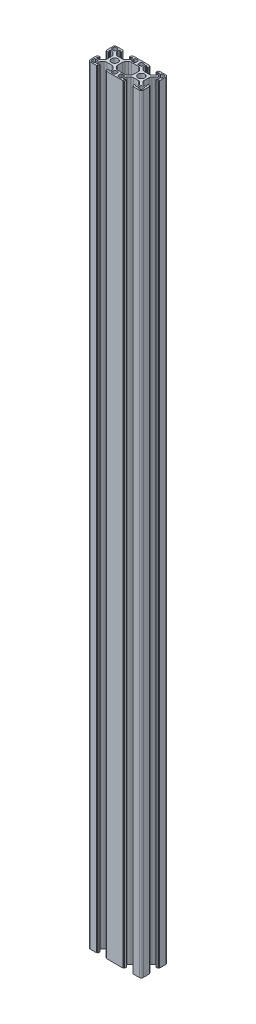
SolidWorks part; units mm, degrees
ref_plane "Спереди" through (0, 0, 0) normal (0, 0, 1) x (1, 0, 0)
ref_plane "Сверху" through (0, 0, 0) normal (0, 1, 0) x (1, 0, 0)
ref_plane "Справа" through (0, 0, 0) normal (1, 0, 0) x (0, 0, -1)
sketch "Эскиз1" plane through (0, 0, 0) normal (0, 1, 0) x (1, 0, 0)
  line L0 (-3.1522, 8.2837) -> (-1.6522, 6.7837) construction
  line L1 (18.3478, 9.7837) -> (15.3478, 6.7837) construction
  line L2 (-10.7522, 0.6837) -> (-0.7522, 10.6837) construction
  line L3 (9.2478, 4.6837) -> (11.1466, 4.6837)
  line L4 (9.2478, 0.6837) -> (19.2478, 10.6837) construction
  line L5 (16.8478, 8.2837) -> (15.3478, 9.7837) construction
  line L6 (12.5608, 5.2695) -> (13.862, 6.5707)
  line L7 (16.1478, 6.7837) -> (17.5478, 6.7837)
  line L8 (15.3478, 7.5837) -> (15.3478, 8.9837)
  line L9 (17.5478, 9.7837) -> (16.1478, 9.7837)
  line L10 (14.4478, 8.8837) -> (14.4478, 7.9849)
  line L11 (13.011, 8.757) -> (13.4914, 9.2373)
  line L12 (12.4478, 10.2328) -> (12.9478, 10.2328)
  line L13 (12.8343, 8.6837) -> (12.5478, 8.6837)
  line L14 (13.8449, 9.3837) -> (13.9478, 9.3837)
  line L15 (12.9478, 10.5337) -> (12.9478, 10.2328)
  line L16 (12.2978, 10.0828) -> (12.2978, 8.9337)
  line L17 (17.7478, 10.6837) -> (13.0978, 10.6837)
  line L18 (18.3478, 8.9837) -> (18.3478, 7.5837)
  line L19 (19.2478, 9.1837) -> (19.2478, 4.5337)
  line L20 (18.6469, 3.7337) -> (17.4978, 3.7337)
  line L21 (19.0978, 4.3837) -> (18.7969, 4.3837)
  line L22 (17.9478, 5.2808) -> (17.9478, 5.3837)
  line L23 (17.2478, 4.2702) -> (17.2478, 3.9837)
  line L24 (18.7969, 3.8837) -> (18.7969, 4.3837)
  line L25 (17.321, 4.447) -> (17.8014, 4.9273)
  line L26 (17.4478, 5.8837) -> (16.549, 5.8837)
  line L27 (13.8336, 3.9967) -> (15.1348, 5.2979)
  line L28 (13.2478, 0.6837) -> (13.2478, 2.5825)
  line L29 (13.2478, 0.6837) -> (13.2478, -1.2151)
  line L30 (13.8336, -2.6293) -> (15.1348, -3.9305)
  line L31 (15.3478, -6.2163) -> (15.3478, -7.6163)
  line L32 (16.1478, -5.4163) -> (17.5478, -5.4163)
  line L33 (18.3478, -7.6163) -> (18.3478, -6.2163)
  line L34 (17.4478, -4.5163) -> (16.549, -4.5163)
  line L35 (17.321, -3.0795) -> (17.8014, -3.5598)
  line L36 (18.7969, -2.5163) -> (18.7969, -3.0163)
  line L37 (17.2478, -2.9027) -> (17.2478, -2.6163)
  line L38 (17.9478, -3.9134) -> (17.9478, -4.0163)
  line L39 (19.0978, -3.0163) -> (18.7969, -3.0163)
  line L40 (18.6469, -2.3663) -> (17.4978, -2.3663)
  line L41 (19.2478, -7.8163) -> (19.2478, -3.1663)
  line L42 (17.5478, -8.4163) -> (16.1478, -8.4163)
  line L43 (17.7478, -9.3163) -> (13.0978, -9.3163)
  line L44 (12.2978, -8.7153) -> (12.2978, -7.5663)
  line L45 (12.9478, -9.1663) -> (12.9478, -8.8653)
  line L46 (13.8449, -8.0163) -> (13.9478, -8.0163)
  line L47 (12.8343, -7.3163) -> (12.5478, -7.3163)
  line L48 (12.4478, -8.8653) -> (12.9478, -8.8653)
  line L49 (13.011, -7.3895) -> (13.4914, -7.8698)
  line L50 (14.4478, -7.5163) -> (14.4478, -6.6175)
  line L51 (12.5608, -3.9021) -> (13.862, -5.2033)
  line L52 (9.2478, -3.3163) -> (11.1466, -3.3163)
  line L53 (18.3478, -8.4163) -> (15.3478, -5.4163) construction
  line L54 (9.2478, 0.6837) -> (19.2478, -9.3163) construction
  line L55 (16.8478, -6.9163) -> (18.3478, -5.4163) construction
  line L56 (9.2478, -3.3163) -> (7.349, -3.3163)
  line L57 (5.9348, -3.9021) -> (4.6336, -5.2033)
  line L58 (2.3478, -5.4163) -> (0.9478, -5.4163)
  line L59 (3.1478, -6.2163) -> (3.1478, -7.6163)
  line L60 (0.9478, -8.4163) -> (2.3478, -8.4163)
  line L61 (4.0478, -7.5163) -> (4.0478, -6.6175)
  line L62 (5.4846, -7.3895) -> (5.0043, -7.8698)
  line L63 (6.0478, -8.8653) -> (5.5478, -8.8653)
  line L64 (5.6614, -7.3163) -> (5.9478, -7.3163)
  line L65 (4.6507, -8.0163) -> (4.5478, -8.0163)
  line L66 (5.5478, -9.1663) -> (5.5478, -8.8653)
  line L67 (6.1978, -8.7153) -> (6.1978, -7.5663)
  line L68 (0.7478, -9.3163) -> (5.3978, -9.3163)
  line L69 (0.1478, -7.6163) -> (0.1478, -6.2163)
  line L70 (1.0478, -4.5163) -> (1.9466, -4.5163)
  line L71 (4.662, -2.6293) -> (3.3608, -3.9305)
  line L72 (5.2478, 0.6837) -> (5.2478, -1.2151)
  line L73 (-1.6522, 9.7837) -> (-4.6522, 6.7837) construction
  line L74 (0.1478, -8.4163) -> (3.1478, -5.4163) construction
  line L75 (-3.1522, -6.9163) -> (-4.6522, -8.4163) construction
  line L76 (9.2478, 0.6837) -> (-0.7522, -9.3163) construction
  line L77 (1.6478, -6.9163) -> (3.1478, -8.4163) construction
  line L78 (5.2478, 0.6837) -> (5.2478, 2.5825)
  line L79 (4.662, 3.9967) -> (3.3608, 5.2979)
  line L80 (3.1478, 7.5837) -> (3.1478, 8.9837)
  line L81 (2.3478, 6.7837) -> (0.9478, 6.7837)
  line L82 (0.1478, 8.9837) -> (0.1478, 7.5837)
  line L83 (1.0478, 5.8837) -> (1.9466, 5.8837)
  line L84 (0.9478, 9.7837) -> (2.3478, 9.7837)
  line L85 (0.7478, 10.6837) -> (5.3978, 10.6837)
  line L86 (6.1978, 10.0828) -> (6.1978, 8.9337)
  line L87 (5.5478, 10.5337) -> (5.5478, 10.2328)
  line L88 (4.6507, 9.3837) -> (4.5478, 9.3837)
  line L89 (5.6614, 8.6837) -> (5.9478, 8.6837)
  line L90 (6.0478, 10.2328) -> (5.5478, 10.2328)
  line L91 (5.4846, 8.757) -> (5.0043, 9.2373)
  line L92 (4.0478, 8.8837) -> (4.0478, 7.9849)
  line L93 (5.9348, 5.2695) -> (4.6336, 6.5707)
  line L94 (9.2478, 4.6837) -> (7.349, 4.6837)
  line L95 (-2.5162, 0.6837) -> (20.7522, 0.6837) construction
  line L96 (0.1478, 9.7837) -> (3.1478, 6.7837) construction
  line L97 (9.2478, -11.4027) -> (9.2478, 11.4027) construction
  line L98 (9.2478, 0.6837) -> (-0.7522, 10.6837) construction
  line L99 (1.6478, 8.2837) -> (0.1478, 6.7837) construction
  line L100 (-10.7522, 0.6837) -> (-0.7522, -9.3163) construction
  line L101 (-1.6522, -8.4163) -> (-4.6522, -5.4163) construction
  line L102 (-18.3522, -6.9163) -> (-19.8522, -5.4163) construction
  line L103 (-10.7522, 0.6837) -> (-20.7522, -9.3163) construction
  line L104 (-19.8522, -8.4163) -> (-16.8522, -5.4163) construction
  line L105 (-18.3522, 8.2837) -> (-16.8522, 9.7837) construction
  line L106 (-10.7522, 0.6837) -> (-20.7522, 10.6837) construction
  line L107 (-19.8522, 9.7837) -> (-16.8522, 6.7837) construction
  line L108 (-10.7522, 4.6837) -> (-8.8534, 4.6837)
  line L109 (-7.4392, 5.2695) -> (-6.138, 6.5707)
  line L110 (-5.5522, 8.8837) -> (-5.5522, 7.9849)
  line L111 (-6.989, 8.757) -> (-6.5086, 9.2373)
  line L112 (-7.5522, 10.2328) -> (-7.0522, 10.2328)
  line L113 (-7.1657, 8.6837) -> (-7.4522, 8.6837)
  line L114 (-6.1551, 9.3837) -> (-6.0522, 9.3837)
  line L115 (-7.0522, 10.5337) -> (-7.0522, 10.2328)
  line L116 (-7.7022, 10.0828) -> (-7.7022, 8.9337)
  line L117 (-2.2522, 10.6837) -> (-6.9022, 10.6837)
  line L118 (-2.4522, 9.7837) -> (-3.8522, 9.7837)
  line L119 (-2.5522, 5.8837) -> (-3.451, 5.8837)
  line L120 (-1.6522, 8.9837) -> (-1.6522, 7.5837)
  line L121 (-3.8522, 6.7837) -> (-2.4522, 6.7837)
  line L122 (-4.6522, 7.5837) -> (-4.6522, 8.9837)
  line L123 (-6.1664, 3.9967) -> (-4.8652, 5.2979)
  line L124 (-6.7522, 0.6837) -> (-6.7522, 2.5825)
  line L125 (-6.7522, 0.6837) -> (-6.7522, -1.2151)
  line L126 (-6.1664, -2.6293) -> (-4.8652, -3.9305)
  line L127 (-2.5522, -4.5163) -> (-3.451, -4.5163)
  line L128 (-1.6522, -7.6163) -> (-1.6522, -6.2163)
  line L129 (-2.2522, -9.3163) -> (-6.9022, -9.3163)
  line L130 (-7.7022, -8.7153) -> (-7.7022, -7.5663)
  line L131 (-7.0522, -9.1663) -> (-7.0522, -8.8653)
  line L132 (-6.1551, -8.0163) -> (-6.0522, -8.0163)
  line L133 (-7.1657, -7.3163) -> (-7.4522, -7.3163)
  line L134 (-7.5522, -8.8653) -> (-7.0522, -8.8653)
  line L135 (-6.989, -7.3895) -> (-6.5086, -7.8698)
  line L136 (-5.5522, -7.5163) -> (-5.5522, -6.6175)
  line L137 (-2.4522, -8.4163) -> (-3.8522, -8.4163)
  line L138 (-4.6522, -6.2163) -> (-4.6522, -7.6163)
  line L139 (-3.8522, -5.4163) -> (-2.4522, -5.4163)
  line L140 (-7.4392, -3.9021) -> (-6.138, -5.2033)
  line L141 (-10.7522, -3.3163) -> (-8.8534, -3.3163)
  line L142 (-10.7522, -3.3163) -> (-12.651, -3.3163)
  line L143 (-14.0652, -3.9021) -> (-15.3664, -5.2033)
  line L144 (-15.9522, -7.5163) -> (-15.9522, -6.6175)
  line L145 (-14.5154, -7.3895) -> (-14.9957, -7.8698)
  line L146 (-13.9522, -8.8653) -> (-14.4522, -8.8653)
  line L147 (-14.3386, -7.3163) -> (-14.0522, -7.3163)
  line L148 (-15.3493, -8.0163) -> (-15.4522, -8.0163)
  line L149 (-14.4522, -9.1663) -> (-14.4522, -8.8653)
  line L150 (-13.8022, -8.7153) -> (-13.8022, -7.5663)
  line L151 (-19.2522, -9.3163) -> (-14.6022, -9.3163)
  line L152 (-19.0522, -8.4163) -> (-17.6522, -8.4163)
  line L153 (-20.7522, -7.8163) -> (-20.7522, -3.1663)
  line L154 (-20.1512, -2.3663) -> (-19.0022, -2.3663)
  line L155 (-20.6022, -3.0163) -> (-20.3012, -3.0163)
  line L156 (-19.4522, -3.9134) -> (-19.4522, -4.0163)
  line L157 (-18.7522, -2.9027) -> (-18.7522, -2.6163)
  line L158 (-20.3012, -2.5163) -> (-20.3012, -3.0163)
  line L159 (-18.8254, -3.0795) -> (-19.3057, -3.5598)
  line L160 (-18.9522, -4.5163) -> (-18.0534, -4.5163)
  line L161 (-19.8522, -7.6163) -> (-19.8522, -6.2163)
  line L162 (-17.6522, -5.4163) -> (-19.0522, -5.4163)
  line L163 (-16.8522, -6.2163) -> (-16.8522, -7.6163)
  line L164 (-15.338, -2.6293) -> (-16.6392, -3.9305)
  line L165 (-14.7522, 0.6837) -> (-14.7522, -1.2151)
  line L166 (-14.7522, 0.6837) -> (-14.7522, 2.5825)
  line L167 (-15.338, 3.9967) -> (-16.6392, 5.2979)
  line L168 (-18.9522, 5.8837) -> (-18.0534, 5.8837)
  line L169 (-18.8254, 4.447) -> (-19.3057, 4.9273)
  line L170 (-20.3012, 3.8837) -> (-20.3012, 4.3837)
  line L171 (-18.7522, 4.2702) -> (-18.7522, 3.9837)
  line L172 (-19.4522, 5.2808) -> (-19.4522, 5.3837)
  line L173 (-20.6022, 4.3837) -> (-20.3012, 4.3837)
  line L174 (-20.1512, 3.7337) -> (-19.0022, 3.7337)
  line L175 (-20.7522, 9.1837) -> (-20.7522, 4.5337)
  line L176 (-19.8522, 8.9837) -> (-19.8522, 7.5837)
  line L177 (-19.2522, 10.6837) -> (-14.6022, 10.6837)
  line L178 (-13.8022, 10.0828) -> (-13.8022, 8.9337)
  line L179 (-14.4522, 10.5337) -> (-14.4522, 10.2328)
  line L180 (-15.3493, 9.3837) -> (-15.4522, 9.3837)
  line L181 (-14.3386, 8.6837) -> (-14.0522, 8.6837)
  line L182 (-13.9522, 10.2328) -> (-14.4522, 10.2328)
  line L183 (-14.5154, 8.757) -> (-14.9957, 9.2373)
  line L184 (-15.9522, 8.8837) -> (-15.9522, 7.9849)
  line L185 (-19.0522, 9.7837) -> (-17.6522, 9.7837)
  line L186 (-16.8522, 7.5837) -> (-16.8522, 8.9837)
  line L187 (-17.6522, 6.7837) -> (-19.0522, 6.7837)
  line L188 (-14.0652, 5.2695) -> (-15.3664, 6.5707)
  line L189 (-10.7522, 4.6837) -> (-12.651, 4.6837)
  line L190 (-2.2522, -9.3163) -> (0.7478, -9.3163)
  line L191 (-2.5522, -4.5163) -> (1.0478, -4.5163)
  line L192 (-2.5522, 5.8837) -> (1.0478, 5.8837)
  line L193 (-2.2522, 10.6837) -> (0.7478, 10.6837)
  arc A0 (18.3478, 8.9837) -> (17.5478, 9.7837) centre (17.5478, 8.9837) ccw
  arc A1 (16.1478, 9.7837) -> (15.3478, 8.9837) centre (16.1478, 8.9837) ccw
  arc A2 (16.1478, 6.7837) -> (15.3478, 7.5837) centre (16.1478, 7.5837) cw
  arc A3 (17.7478, 10.6837) -> (19.2478, 9.1837) centre (17.7478, 9.1837) cw
  arc A4 (12.4478, 10.2328) -> (12.2978, 10.0828) centre (12.4478, 10.0828) ccw
  arc A5 (13.0978, 10.6837) -> (12.9478, 10.5337) centre (13.0978, 10.5337) ccw
  arc A6 (12.8343, 8.6837) -> (13.011, 8.757) centre (12.8343, 8.9337) ccw
  arc A7 (12.5478, 8.6837) -> (12.2978, 8.9337) centre (12.5478, 8.9337) cw
  arc A8 (13.4914, 9.2373) -> (13.8449, 9.3837) centre (13.8449, 8.8837) cw
  arc A9 (13.9478, 9.3837) -> (14.4478, 8.8837) centre (13.9478, 8.8837) cw
  arc A10 (11.7478, 0.6837) -> (9.2478, 3.1837) centre (9.2478, 0.6837) ccw
  arc A11 (11.1466, 4.6837) -> (12.5608, 5.2695) centre (11.1466, 6.6837) ccw
  arc A12 (14.4478, 7.9849) -> (13.862, 6.5707) centre (12.4478, 7.9849) cw
  arc A13 (18.3478, 7.5837) -> (17.5478, 6.7837) centre (17.5478, 7.5837) cw
  arc A14 (17.9478, 5.3837) -> (17.4478, 5.8837) centre (17.4478, 5.3837) ccw
  arc A15 (17.8014, 4.9273) -> (17.9478, 5.2808) centre (17.4478, 5.2808) ccw
  arc A16 (17.2478, 3.9837) -> (17.4978, 3.7337) centre (17.4978, 3.9837) ccw
  arc A17 (17.2478, 4.2702) -> (17.321, 4.447) centre (17.4978, 4.2702) cw
  arc A18 (19.2478, 4.5337) -> (19.0978, 4.3837) centre (19.0978, 4.5337) cw
  arc A19 (18.7969, 3.8837) -> (18.6469, 3.7337) centre (18.6469, 3.8837) cw
  arc A20 (16.549, 5.8837) -> (15.1348, 5.2979) centre (16.549, 3.8837) ccw
  arc A21 (13.2478, 2.5825) -> (13.8336, 3.9967) centre (15.2478, 2.5825) cw
  arc A22 (17.5478, -8.4163) -> (18.3478, -7.6163) centre (17.5478, -7.6163) ccw
  arc A23 (18.3478, -6.2163) -> (17.5478, -5.4163) centre (17.5478, -6.2163) ccw
  arc A24 (15.3478, -6.2163) -> (16.1478, -5.4163) centre (16.1478, -6.2163) cw
  arc A25 (19.2478, -7.8163) -> (17.7478, -9.3163) centre (17.7478, -7.8163) cw
  arc A26 (18.7969, -2.5163) -> (18.6469, -2.3663) centre (18.6469, -2.5163) ccw
  arc A27 (19.2478, -3.1663) -> (19.0978, -3.0163) centre (19.0978, -3.1663) ccw
  arc A28 (17.2478, -2.9027) -> (17.321, -3.0795) centre (17.4978, -2.9027) ccw
  arc A29 (17.2478, -2.6163) -> (17.4978, -2.3663) centre (17.4978, -2.6163) cw
  arc A30 (17.8014, -3.5598) -> (17.9478, -3.9134) centre (17.4478, -3.9134) cw
  arc A31 (17.9478, -4.0163) -> (17.4478, -4.5163) centre (17.4478, -4.0163) cw
  arc A32 (9.2478, -1.8163) -> (11.7478, 0.6837) centre (9.2478, 0.6837) ccw
  arc A33 (13.2478, -1.2151) -> (13.8336, -2.6293) centre (15.2478, -1.2151) ccw
  arc A34 (16.549, -4.5163) -> (15.1348, -3.9305) centre (16.549, -2.5163) cw
  arc A35 (16.1478, -8.4163) -> (15.3478, -7.6163) centre (16.1478, -7.6163) cw
  arc A36 (13.9478, -8.0163) -> (14.4478, -7.5163) centre (13.9478, -7.5163) ccw
  arc A37 (13.4914, -7.8698) -> (13.8449, -8.0163) centre (13.8449, -7.5163) ccw
  arc A38 (12.5478, -7.3163) -> (12.2978, -7.5663) centre (12.5478, -7.5663) ccw
  arc A39 (12.8343, -7.3163) -> (13.011, -7.3895) centre (12.8343, -7.5663) cw
  arc A40 (13.0978, -9.3163) -> (12.9478, -9.1663) centre (13.0978, -9.1663) cw
  arc A41 (12.4478, -8.8653) -> (12.2978, -8.7153) centre (12.4478, -8.7153) cw
  arc A42 (14.4478, -6.6175) -> (13.862, -5.2033) centre (12.4478, -6.6175) ccw
  arc A43 (11.1466, -3.3163) -> (12.5608, -3.9021) centre (11.1466, -5.3163) cw
  arc A44 (0.1478, -7.6163) -> (0.9478, -8.4163) centre (0.9478, -7.6163) ccw
  arc A45 (2.3478, -8.4163) -> (3.1478, -7.6163) centre (2.3478, -7.6163) ccw
  arc A46 (2.3478, -5.4163) -> (3.1478, -6.2163) centre (2.3478, -6.2163) cw
  arc A47 (6.0478, -8.8653) -> (6.1978, -8.7153) centre (6.0478, -8.7153) ccw
  arc A48 (5.3978, -9.3163) -> (5.5478, -9.1663) centre (5.3978, -9.1663) ccw
  arc A49 (5.6614, -7.3163) -> (5.4846, -7.3895) centre (5.6614, -7.5663) ccw
  arc A50 (5.9478, -7.3163) -> (6.1978, -7.5663) centre (5.9478, -7.5663) cw
  arc A51 (5.0043, -7.8698) -> (4.6507, -8.0163) centre (4.6507, -7.5163) cw
  arc A52 (4.5478, -8.0163) -> (4.0478, -7.5163) centre (4.5478, -7.5163) cw
  arc A53 (6.7478, 0.6837) -> (9.2478, -1.8163) centre (9.2478, 0.6837) ccw
  arc A54 (7.349, -3.3163) -> (5.9348, -3.9021) centre (7.349, -5.3163) ccw
  arc A55 (4.0478, -6.6175) -> (4.6336, -5.2033) centre (6.0478, -6.6175) cw
  arc A56 (0.1478, -6.2163) -> (0.9478, -5.4163) centre (0.9478, -6.2163) cw
  arc A57 (1.9466, -4.5163) -> (3.3608, -3.9305) centre (1.9466, -2.5163) ccw
  arc A58 (5.2478, -1.2151) -> (4.662, -2.6293) centre (3.2478, -1.2151) cw
  arc A59 (0.9478, 9.7837) -> (0.1478, 8.9837) centre (0.9478, 8.9837) ccw
  arc A60 (0.1478, 7.5837) -> (0.9478, 6.7837) centre (0.9478, 7.5837) ccw
  arc A61 (3.1478, 7.5837) -> (2.3478, 6.7837) centre (2.3478, 7.5837) cw
  arc A62 (9.2478, 3.1837) -> (6.7478, 0.6837) centre (9.2478, 0.6837) ccw
  arc A63 (5.2478, 2.5825) -> (4.662, 3.9967) centre (3.2478, 2.5825) ccw
  arc A64 (1.9466, 5.8837) -> (3.3608, 5.2979) centre (1.9466, 3.8837) cw
  arc A65 (2.3478, 9.7837) -> (3.1478, 8.9837) centre (2.3478, 8.9837) cw
  arc A66 (4.5478, 9.3837) -> (4.0478, 8.8837) centre (4.5478, 8.8837) ccw
  arc A67 (5.0043, 9.2373) -> (4.6507, 9.3837) centre (4.6507, 8.8837) ccw
  arc A68 (5.9478, 8.6837) -> (6.1978, 8.9337) centre (5.9478, 8.9337) ccw
  arc A69 (5.6614, 8.6837) -> (5.4846, 8.757) centre (5.6614, 8.9337) cw
  arc A70 (5.3978, 10.6837) -> (5.5478, 10.5337) centre (5.3978, 10.5337) cw
  arc A71 (6.0478, 10.2328) -> (6.1978, 10.0828) centre (6.0478, 10.0828) cw
  arc A72 (4.0478, 7.9849) -> (4.6336, 6.5707) centre (6.0478, 7.9849) ccw
  arc A73 (7.349, 4.6837) -> (5.9348, 5.2695) centre (7.349, 6.6837) cw
  arc A74 (-8.8534, 4.6837) -> (-7.4392, 5.2695) centre (-8.8534, 6.6837) ccw
  arc A75 (-5.5522, 7.9849) -> (-6.138, 6.5707) centre (-7.5522, 7.9849) cw
  arc A76 (-7.5522, 10.2328) -> (-7.7022, 10.0828) centre (-7.5522, 10.0828) ccw
  arc A77 (-6.9022, 10.6837) -> (-7.0522, 10.5337) centre (-6.9022, 10.5337) ccw
  arc A78 (-7.1657, 8.6837) -> (-6.989, 8.757) centre (-7.1657, 8.9337) ccw
  arc A79 (-7.4522, 8.6837) -> (-7.7022, 8.9337) centre (-7.4522, 8.9337) cw
  arc A80 (-6.5086, 9.2373) -> (-6.1551, 9.3837) centre (-6.1551, 8.8837) cw
  arc A81 (-6.0522, 9.3837) -> (-5.5522, 8.8837) centre (-6.0522, 8.8837) cw
  arc A82 (-3.8522, 9.7837) -> (-4.6522, 8.9837) centre (-3.8522, 8.9837) ccw
  arc A83 (-3.451, 5.8837) -> (-4.8652, 5.2979) centre (-3.451, 3.8837) ccw
  arc A84 (-6.7522, 2.5825) -> (-6.1664, 3.9967) centre (-4.7522, 2.5825) cw
  arc A85 (-10.7522, 3.1837) -> (-8.2522, 0.6837) centre (-10.7522, 0.6837) cw
  arc A86 (-4.6522, 7.5837) -> (-3.8522, 6.7837) centre (-3.8522, 7.5837) ccw
  arc A87 (-1.6522, 7.5837) -> (-2.4522, 6.7837) centre (-2.4522, 7.5837) cw
  arc A88 (-2.4522, 9.7837) -> (-1.6522, 8.9837) centre (-2.4522, 8.9837) cw
  arc A89 (-6.7522, -1.2151) -> (-6.1664, -2.6293) centre (-4.7522, -1.2151) ccw
  arc A90 (-3.451, -4.5163) -> (-4.8652, -3.9305) centre (-3.451, -2.5163) cw
  arc A91 (-1.6522, -6.2163) -> (-2.4522, -5.4163) centre (-2.4522, -6.2163) ccw
  arc A92 (-5.5522, -6.6175) -> (-6.138, -5.2033) centre (-7.5522, -6.6175) ccw
  arc A93 (-8.8534, -3.3163) -> (-7.4392, -3.9021) centre (-8.8534, -5.3163) cw
  arc A94 (-8.2522, 0.6837) -> (-10.7522, -1.8163) centre (-10.7522, 0.6837) cw
  arc A95 (-6.0522, -8.0163) -> (-5.5522, -7.5163) centre (-6.0522, -7.5163) ccw
  arc A96 (-6.5086, -7.8698) -> (-6.1551, -8.0163) centre (-6.1551, -7.5163) ccw
  arc A97 (-7.4522, -7.3163) -> (-7.7022, -7.5663) centre (-7.4522, -7.5663) ccw
  arc A98 (-7.1657, -7.3163) -> (-6.989, -7.3895) centre (-7.1657, -7.5663) cw
  arc A99 (-6.9022, -9.3163) -> (-7.0522, -9.1663) centre (-6.9022, -9.1663) cw
  arc A100 (-7.5522, -8.8653) -> (-7.7022, -8.7153) centre (-7.5522, -8.7153) cw
  arc A101 (-3.8522, -5.4163) -> (-4.6522, -6.2163) centre (-3.8522, -6.2163) ccw
  arc A102 (-3.8522, -8.4163) -> (-4.6522, -7.6163) centre (-3.8522, -7.6163) cw
  arc A103 (-1.6522, -7.6163) -> (-2.4522, -8.4163) centre (-2.4522, -7.6163) cw
  arc A104 (-12.651, -3.3163) -> (-14.0652, -3.9021) centre (-12.651, -5.3163) ccw
  arc A105 (-15.9522, -6.6175) -> (-15.3664, -5.2033) centre (-13.9522, -6.6175) cw
  arc A106 (-13.9522, -8.8653) -> (-13.8022, -8.7153) centre (-13.9522, -8.7153) ccw
  arc A107 (-14.6022, -9.3163) -> (-14.4522, -9.1663) centre (-14.6022, -9.1663) ccw
  arc A108 (-14.3386, -7.3163) -> (-14.5154, -7.3895) centre (-14.3386, -7.5663) ccw
  arc A109 (-14.0522, -7.3163) -> (-13.8022, -7.5663) centre (-14.0522, -7.5663) cw
  arc A110 (-14.9957, -7.8698) -> (-15.3493, -8.0163) centre (-15.3493, -7.5163) cw
  arc A111 (-15.4522, -8.0163) -> (-15.9522, -7.5163) centre (-15.4522, -7.5163) cw
  arc A112 (-17.6522, -8.4163) -> (-16.8522, -7.6163) centre (-17.6522, -7.6163) ccw
  arc A113 (-18.0534, -4.5163) -> (-16.6392, -3.9305) centre (-18.0534, -2.5163) ccw
  arc A114 (-14.7522, -1.2151) -> (-15.338, -2.6293) centre (-16.7522, -1.2151) cw
  arc A115 (-10.7522, -1.8163) -> (-13.2522, 0.6837) centre (-10.7522, 0.6837) cw
  arc A116 (-19.4522, -4.0163) -> (-18.9522, -4.5163) centre (-18.9522, -4.0163) ccw
  arc A117 (-19.3057, -3.5598) -> (-19.4522, -3.9134) centre (-18.9522, -3.9134) ccw
  arc A118 (-18.7522, -2.6163) -> (-19.0022, -2.3663) centre (-19.0022, -2.6163) ccw
  arc A119 (-18.7522, -2.9027) -> (-18.8254, -3.0795) centre (-19.0022, -2.9027) cw
  arc A120 (-20.7522, -3.1663) -> (-20.6022, -3.0163) centre (-20.6022, -3.1663) cw
  arc A121 (-20.3012, -2.5163) -> (-20.1512, -2.3663) centre (-20.1512, -2.5163) cw
  arc A122 (-20.7522, -7.8163) -> (-19.2522, -9.3163) centre (-19.2522, -7.8163) ccw
  arc A123 (-16.8522, -6.2163) -> (-17.6522, -5.4163) centre (-17.6522, -6.2163) ccw
  arc A124 (-19.8522, -6.2163) -> (-19.0522, -5.4163) centre (-19.0522, -6.2163) cw
  arc A125 (-19.0522, -8.4163) -> (-19.8522, -7.6163) centre (-19.0522, -7.6163) cw
  arc A126 (-14.7522, 2.5825) -> (-15.338, 3.9967) centre (-16.7522, 2.5825) ccw
  arc A127 (-18.0534, 5.8837) -> (-16.6392, 5.2979) centre (-18.0534, 3.8837) cw
  arc A128 (-20.3012, 3.8837) -> (-20.1512, 3.7337) centre (-20.1512, 3.8837) ccw
  arc A129 (-20.7522, 4.5337) -> (-20.6022, 4.3837) centre (-20.6022, 4.5337) ccw
  arc A130 (-18.7522, 4.2702) -> (-18.8254, 4.447) centre (-19.0022, 4.2702) ccw
  arc A131 (-18.7522, 3.9837) -> (-19.0022, 3.7337) centre (-19.0022, 3.9837) cw
  arc A132 (-19.3057, 4.9273) -> (-19.4522, 5.2808) centre (-18.9522, 5.2808) cw
  arc A133 (-19.4522, 5.3837) -> (-18.9522, 5.8837) centre (-18.9522, 5.3837) cw
  arc A134 (-19.8522, 7.5837) -> (-19.0522, 6.7837) centre (-19.0522, 7.5837) ccw
  arc A135 (-15.9522, 7.9849) -> (-15.3664, 6.5707) centre (-13.9522, 7.9849) ccw
  arc A136 (-12.651, 4.6837) -> (-14.0652, 5.2695) centre (-12.651, 6.6837) cw
  arc A137 (-13.2522, 0.6837) -> (-10.7522, 3.1837) centre (-10.7522, 0.6837) cw
  arc A138 (-15.4522, 9.3837) -> (-15.9522, 8.8837) centre (-15.4522, 8.8837) ccw
  arc A139 (-14.9957, 9.2373) -> (-15.3493, 9.3837) centre (-15.3493, 8.8837) ccw
  arc A140 (-14.0522, 8.6837) -> (-13.8022, 8.9337) centre (-14.0522, 8.9337) ccw
  arc A141 (-14.3386, 8.6837) -> (-14.5154, 8.757) centre (-14.3386, 8.9337) cw
  arc A142 (-14.6022, 10.6837) -> (-14.4522, 10.5337) centre (-14.6022, 10.5337) cw
  arc A143 (-13.9522, 10.2328) -> (-13.8022, 10.0828) centre (-13.9522, 10.0828) cw
  arc A144 (-19.2522, 10.6837) -> (-20.7522, 9.1837) centre (-19.2522, 9.1837) ccw
  arc A145 (-17.6522, 6.7837) -> (-16.8522, 7.5837) centre (-17.6522, 7.5837) ccw
  arc A146 (-17.6522, 9.7837) -> (-16.8522, 8.9837) centre (-17.6522, 8.9837) cw
  arc A147 (-19.8522, 8.9837) -> (-19.0522, 9.7837) centre (-19.0522, 8.9837) cw
  point P0 (9.2478, 0.6837)
  point P12 (9.2478, 0.6837)
  point P45 (17.9478, 4.3837)
  point P104 (12.9478, -8.0163)
  point P155 (12.9478, 9.3837)
  point P163 (17.9478, -3.0163)
  point P164 (9.2478, -3.2405)
  point P166 (9.2478, 0.6837)
  point P224 (5.5478, -8.0163)
  point P225 (5.3236, 0.6837)
  point P227 (9.2478, 0.6837)
  point P267 (5.5478, 9.3837)
  point P272 (13.1721, 0.6837)
  point P288 (9.2478, 4.608)
  point P290 (9.2478, 0.6837)
  point P515 (-10.7522, 4.608)
  point P516 (-14.6764, 0.6837)
  point P517 (-7.0522, 9.3837)
  point P518 (-6.8279, 0.6837)
  point P519 (-7.0522, -8.0163)
  point P520 (-10.7522, -3.2405)
  point P521 (-19.4522, -3.0163)
  point P522 (-14.4522, 9.3837)
  point P523 (-14.4522, -8.0163)
  point P524 (-19.4522, 4.3837)
extrude "Бобышка-Вытянуть1" add sketch "Эскиз1" along normal blind 579
